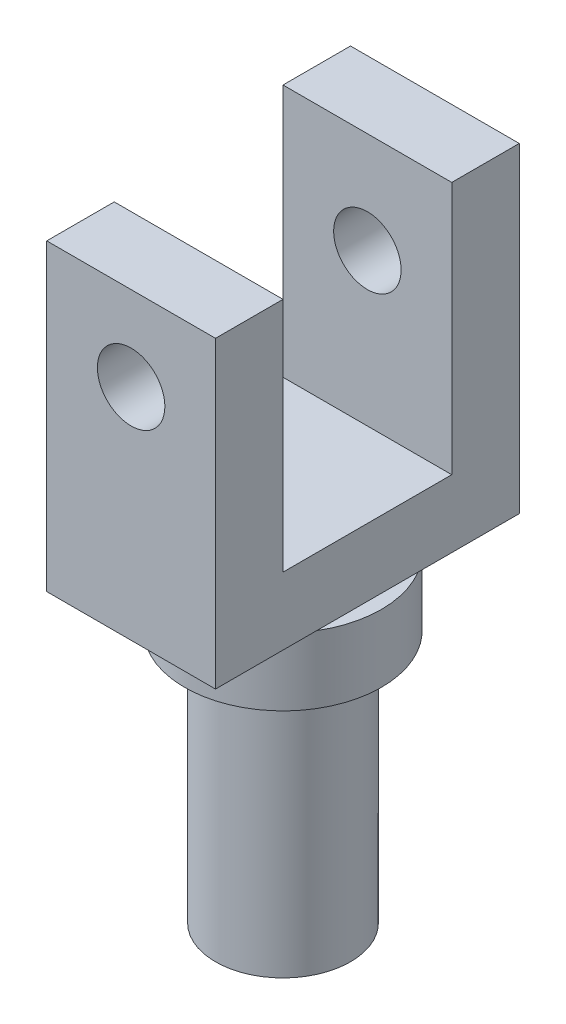
SolidWorks part; units mm, degrees
ref_plane "Plan de face" through (0, 0, 0) normal (0, 0, 1) x (1, 0, 0)
ref_plane "Plan de dessus" through (0, 0, 0) normal (0, 1, 0) x (1, 0, 0)
ref_plane "Plan de droite" through (0, 0, 0) normal (1, 0, 0) x (0, 0, -1)
sketch "Esquisse1" plane through (0, 0, 0) normal (0, 0, 1) x (1, 0, 0)
  line L0 (-295.8452, 25) -> (-245.8452, -25) construction
  line L1 (-295.8452, 25) -> (-245.8452, 25)
  line L2 (-295.8452, 25) -> (-295.8452, -45)
  line L3 (-295.8452, -45) -> (-245.8452, -45)
  line L4 (-245.8452, 25) -> (-245.8452, -45)
  circle A1 centre (-270.8452, 0) radius 10
  dimension "D1" = 45
  dimension "D2" = 50
  dimension "D3" = 70
extrude "Boss.-Extru.1" add sketch "Esquisse1" along normal blind 20
sketch "Esquisse2" plane through (0, -45, 0) normal (0, -1, 0) x (1, 0, 0)
  line L0 (-245.8452, 20) -> (-245.8452, 0) construction
  line L1 (-245.8452, 20) -> (-295.8452, 20)
  line L2 (-245.8452, 20) -> (-245.8452, -70)
  line L3 (-245.8452, -70) -> (-295.8452, -70)
  line L4 (-295.8452, 20) -> (-295.8452, -70)
  dimension "D1" = 90
extrude "Boss.-Extru.2" add sketch "Esquisse2" along normal blind 20
sketch "Esquisse3" plane through (0, -65, 0) normal (0, -1, 0) x (1, 0, 0)
  line L0 (-245.8452, -25) -> (-295.8452, -25) construction
  line L1 (-245.8452, -50) -> (-295.8452, -50) construction
  line L2 (-255.8452, 0) -> (-285.8452, -50) construction
  line L3 (-255.8452, 0) -> (-285.8452, 0) construction
  line L4 (-245.8452, -70) -> (-245.8452, 20)
  line L5 (-245.8452, 20) -> (-295.8452, 20)
  line L6 (-295.8452, 20) -> (-295.8452, -70)
  line L7 (-295.8452, -70) -> (-245.8452, -70)
  line L8 (-245.8452, -70) -> (-245.8452, 20)
  line L9 (-245.8452, 20) -> (-295.8452, 20)
  line L10 (-295.8452, 20) -> (-295.8452, -70)
  line L11 (-295.8452, -70) -> (-245.8452, -70)
  line L12 (-295.8452, 0) -> (-295.8452, -70)
  line L13 (-245.8452, 0) -> (-295.8452, 0)
  line L14 (-245.8452, -70) -> (-245.8452, 0)
  line L15 (-295.8452, -70) -> (-245.8452, -70)
  line L16 (-295.8452, 0) -> (-295.8452, -70)
  line L17 (-245.8452, 0) -> (-295.8452, 0) construction
  line L18 (-245.8452, -70) -> (-245.8452, 0)
  line L19 (-295.8452, -70) -> (-245.8452, -70)
  line L20 (-255.8452, 0) -> (-255.8452, -50) construction
  line L21 (-255.8452, -50) -> (-285.8452, -50)
  line L22 (-285.8452, 0) -> (-285.8452, -50) construction
  circle A0 centre (-270.8452, -25) radius 29.1548
  point P14 (-270.8452, 0)
  dimension "D3" = 30
  dimension "D1" = 0
  dimension "D2" = 0
extrude "Boss.-Extru.3" add sketch "Esquisse3" along normal blind 20 contours A0
sketch "Esquisse4" plane through (0, -85, 0) normal (0, -1, 0) x (1, 0, 0)
  circle A0 centre (-270.8452, -25) radius 20
  dimension "D1" = 40
extrude "Boss.-Extru.4" add sketch "Esquisse4" along normal blind 75
sketch "Esquisse5" plane through (0, -45, 0) normal (0, 1, 0) x (1, 0, 0)
  line L0 (-295.8452, 0) -> (-245.8452, 0) construction
  line L1 (-295.8452, 0) -> (-245.8452, 0)
  line L2 (-245.8452, 70) -> (-245.8452, 40) construction
  line L3 (-245.8452, 40) -> (-245.8452, 10) construction
  line L4 (-245.8452, 10) -> (-245.8452, -20) construction
  line L5 (-245.8452, 70) -> (-245.8452, 40)
  line L6 (-245.8452, 40) -> (-245.8452, 10)
  line L7 (-245.8452, 10) -> (-245.8452, -20)
  line L8 (-245.8452, 25) -> (-304.5923, 25) construction
  line L9 (-295.8452, 50) -> (-245.8452, 50)
  line L10 (-295.8452, 0) -> (-295.8452, 70) construction
  line L11 (-295.8452, 70) -> (-245.8452, 70) construction
  line L12 (-295.8452, 0) -> (-295.8452, 70)
  line L13 (-295.8452, 70) -> (-245.8452, 70)
  line M4 (-295.8452, 70) -> (-295.8452, 0)
  line M7 (-245.8452, 70) -> (-295.8452, 70)
extrude "Boss.-Extru.5" add sketch "Esquisse5" along normal blind 75 contours L9 L5 M4 M7
sketch "Esquisse6" plane through (0, 0, -70) normal (0, 0, -1) x (-1, 0, 0)
  circle A0 centre (270.8452, 0) radius 10 construction
  circle A1 centre (270.8452, 0) radius 10
extrude "Enlèv. mat.-Extru.1" cut sketch "Esquisse6" against normal blind 75
